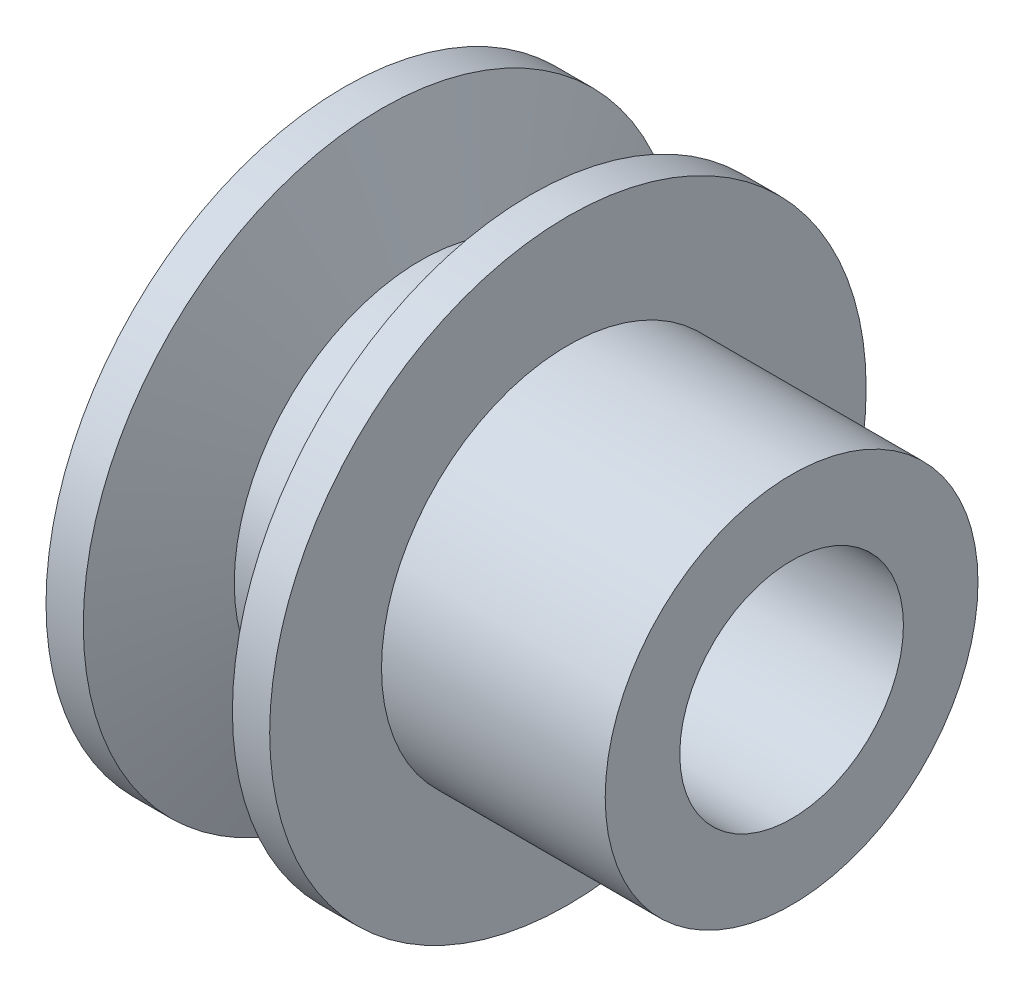
SolidWorks part; units mm, degrees
ref_plane "Front Plane" through (0, 0, 0) normal (0, 0, 1) x (1, 0, 0)
ref_plane "Top Plane" through (0, 0, 0) normal (0, 1, 0) x (1, 0, 0)
ref_plane "Right Plane" through (0, 0, 0) normal (1, 0, 0) x (0, 0, -1)
sketch "Sketch1" plane through (0, 0, 0) normal (0, 0, 1) x (1, 0, 0)
  line L0 (-23.1968, 0) -> (29.6744, 0) construction
  line L1 (-9.3487, 35.2171) -> (-9.3487, 20)
  line L3 (-4.3487, 15) -> (50.6513, 15)
  line L4 (50.6513, 15) -> (50.6513, 25)
  line L5 (50.6513, 25) -> (20.6513, 25)
  line L6 (20.6513, 25) -> (20.6513, 40)
  line L7 (20.6513, 40) -> (15.6513, 40)
  line L8 (15.6513, 40) -> (9.979, 25)
  line L9 (9.979, 25) -> (0.9, 25)
  line L10 (0.9, 25) -> (-4.3487, 40)
  line L11 (-4.3487, 40) -> (-9.3487, 40)
  line L12 (-9.3487, 40) -> (-9.3487, 35.2171)
  line L13 (-9.3487, 20) -> (-4.3487, 15)
  point P6 (-9.3487, 15)
  dimension "D1" = 25
  dimension "D2" = 40
  dimension "D3" = 20
  dimension "D4" = 20
  dimension "D6" = 5
  dimension "D7" = 0.9
  dimension "D8" = 55
  dimension "D9" = 40
  dimension "D10" = 35.2171
  dimension "D11" = 9.979
revolve "Revolve1" add sketch "Sketch1" angle 360 about L0
